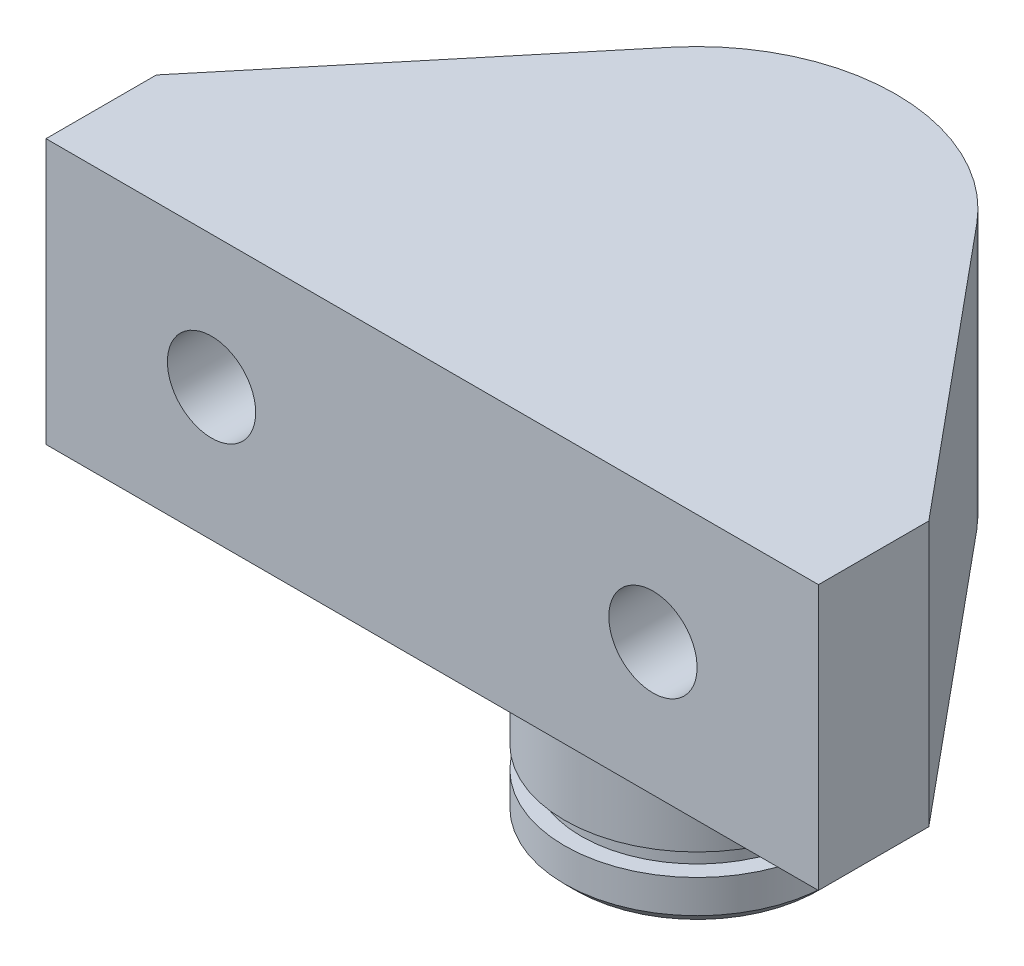
SolidWorks part; units mm, degrees
ref_plane "前视基准面" through (0, 0, 0) normal (0, 0, 1) x (1, 0, 0)
ref_plane "上视基准面" through (0, 0, 0) normal (0, 1, 0) x (1, 0, 0)
ref_plane "右视基准面" through (0, 0, 0) normal (1, 0, 0) x (0, 0, -1)
sketch "草图1" plane through (0, 0, 0) normal (0, 1, 0) x (1, 0, 0)
  line L0 (-40.2621, 0) -> (42.8359, 0) construction
  line L1 (0, 27.1172) -> (0, -30.0587) construction
  line L2 (-17.5, 6.0977) -> (-6.927, 18.8437)
  line L4 (17.5, 6.0977) -> (17.5, 1.0977)
  line L5 (17.5, 1.0977) -> (-17.5, 1.0977)
  line L6 (-17.5, 6.0977) -> (-17.5, 1.0977)
  line L7 (17.5, 6.0977) -> (6.927, 18.8437)
  arc A0 (-6.927, 18.8437) -> (6.927, 18.8437) centre (0, 13.0977) cw
  point P1 (0, 0)
  dimension "D3" = 9
  dimension "D1" = 35
  dimension "D2" = 5
  dimension "D4" = 12
extrude "凸台-拉伸1" add sketch "草图1" along normal blind 12
sketch "草图2" plane through (0, 0, 0) normal (0, 1, 0) x (1, 0, 0)
  line L0 (0, 25.9132) -> (0, -2.6702) construction
  circle A0 centre (0, 13.0977) radius 6
  arc A1 (6.927, 18.8437) -> (-6.927, 18.8437) centre (0, 13.0977) ccw construction
  point P5 (0, 0)
extrude "凸台-拉伸2" add sketch "草图2" against normal blind 9
ref_plane "基准面2" through (0, -9, 0) normal (0, -1, 0) x (-1, 0, 0)
sketch "草图3" plane through (0, -9, 0) normal (0, -1, 0) x (-1, 0, 0)
  line L0 (-16.966, 13.0977) -> (18.1107, 13.0977) construction
  line L1 (0, 24.7208) -> (0, -1.9342) construction
  circle A0 centre (0, 13.0977) radius 5.25
  dimension "D1" = 10.5
extrude "凸台-拉伸3" add sketch "草图3" along normal blind 1
ref_plane "基准面3" through (0, -10, 0) normal (0, -1, 0) x (-1, 0, 0)
sketch "草图4" plane through (0, -10, 0) normal (0, -1, 0) x (-1, 0, 0)
  line L0 (0, 3.871) -> (0, 23.7805) construction
  line L1 (5.25, 13.0977) -> (17.7836, 13.0977) construction
  circle A2 centre (0, 13.0977) radius 6
extrude "凸台-拉伸4" add sketch "草图4" along normal blind 2
chamfer "倒角1" distance 0.5 angle 45 1 edges at (0, -12, -19.0977)
ref_plane "基准面4" through (0, 0, -1.0977) normal (0, 0, 1) x (1, 0, 0)
sketch "草图5" plane through (0, 0, -1.0977) normal (0, 0, 1) x (1, 0, 0)
  line L0 (0, 19.1191) -> (0, -7.9608) construction
  line L1 (1.1746, 6) -> (-25.0031, 6) construction
  line L2 (17.5, 12) -> (17.5, 0) construction
  circle A0 centre (-10, 6) radius 2
  circle A1 centre (10, 6) radius 2
  point P11 (17.5, 6)
  dimension "D1" = 20
extrude "切除-拉伸1" cut sketch "草图5" against normal blind 5
cosmetic thread "装饰螺纹线1" parameters "D2"=12
cosmetic thread "装饰螺纹线2" parameters "D2"=12
